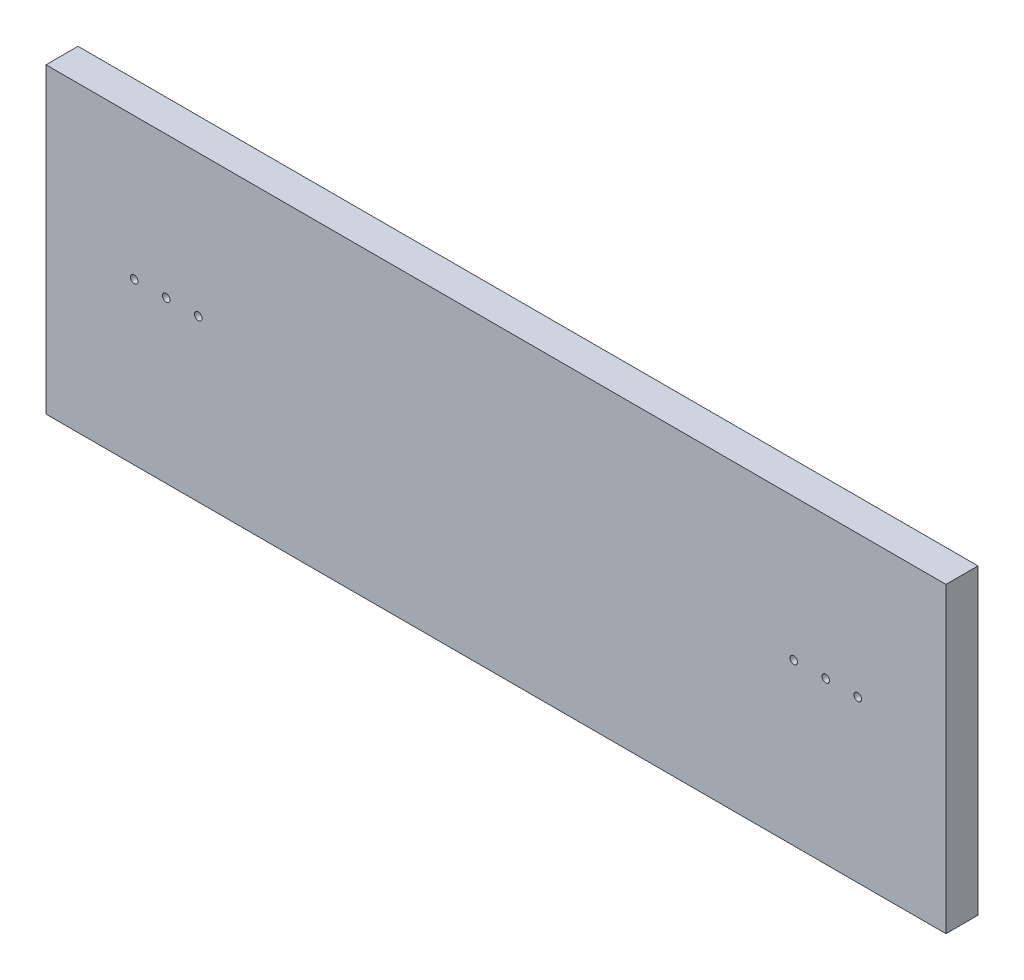
SolidWorks part; units mm, degrees
ref_plane "前视基准面" through (0, 0, 0) normal (0, 0, 1) x (1, 0, 0)
ref_plane "上视基准面" through (0, 0, 0) normal (0, 1, 0) x (1, 0, 0)
ref_plane "右视基准面" through (0, 0, 0) normal (1, 0, 0) x (0, 0, -1)
sketch "草图1" plane through (0, 0, 0) normal (0, 0, 1) x (1, 0, 0)
  line L1 (-178.5, 60) -> (178.5, 60)
  line L2 (-178.5, 60) -> (-178.5, -60)
  line L3 (-178.5, -60) -> (178.5, -60)
  line L4 (178.5, 60) -> (178.5, -60)
  line L5 (-178.5, 60) -> (178.5, -60) construction
  line L6 (-178.5, -60) -> (178.5, 60) construction
  point P0 (0, 0)
  dimension "D1" = 120
  dimension "D2" = 357
extrude "凸台-拉伸1" add sketch "草图1" along normal blind 12.7
sketch "草图2" plane through (0, 0, 12.7) normal (0, 0, 1) x (1, 0, 0)
  line L0 (178.5, -60) -> (178.5, 60) construction
  line L1 (178.5, 60) -> (-178.5, 60) construction
  line L2 (0, 60) -> (0, -60) construction
  line L3 (-178.5, -60) -> (178.5, -60) construction
  line L4 (143.5, 3.8) -> (114.9208, 3.8) construction
  circle A0 centre (143.5, 3.8) radius 1.5
  circle A1 centre (130.8, 3.8) radius 1.5
  circle A2 centre (118.1, 3.8) radius 1.5
  circle A3 centre (-118.1, 3.8) radius 1.5
  circle A4 centre (-130.8, 3.8) radius 1.5
  circle A5 centre (-143.5, 3.8) radius 1.5
  point P20 (130.8, 4.24)
  point P21 (118.1, 4.24)
  dimension "D3" = 3
  dimension "D1" = 12.7
  dimension "D2" = 12.7
  dimension "D4" = 35
  dimension "D5" = 56.2
extrude "切除-拉伸1" cut sketch "草图2" against normal through all
